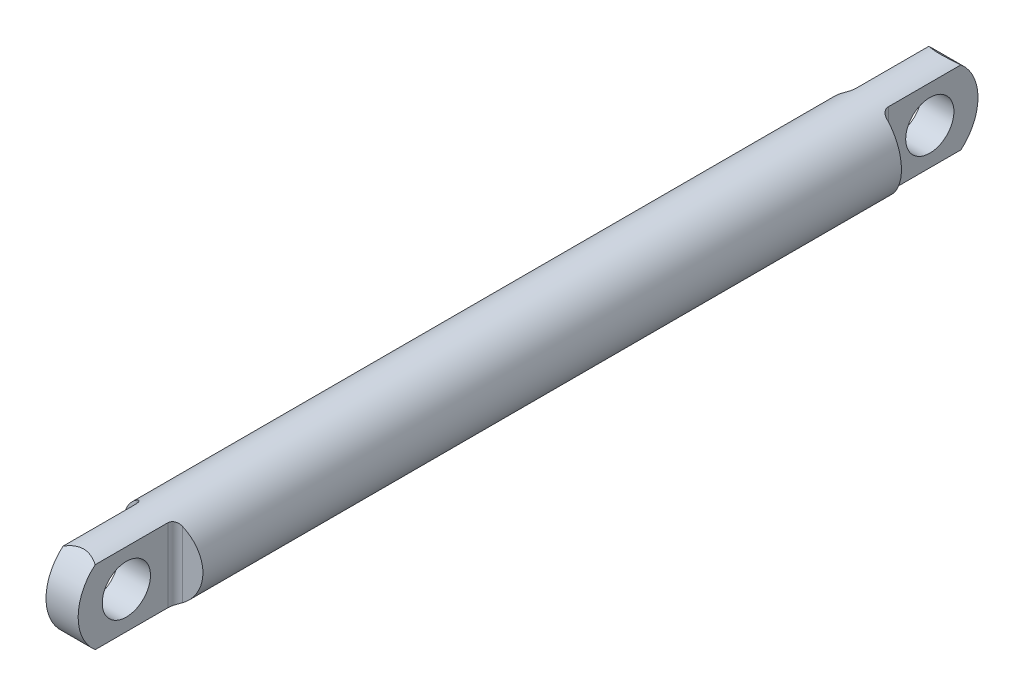
SolidWorks part; units mm, degrees
material "AISI 1045 Steel, cold drawn"
ref_plane "Front Plane" through (0, 0, 0) normal (0, 0, 1) x (1, 0, 0)
ref_plane "Top Plane" through (0, 0, 0) normal (0, 1, 0) x (1, 0, 0)
ref_plane "Right Plane" through (0, 0, 0) normal (1, 0, 0) x (0, 0, -1)
sketch "Sketch1" plane through (0, 0, 0) normal (0, 0, 1) x (1, 0, 0)
  circle A0 centre (0, 0) radius 5
  dimension "D1" = 10
extrude "Boss-Extrude1" add sketch "Sketch1" along normal mid plane 112
sketch "Sketch6" plane through (0, 0, 0) normal (1, 0, 0) x (0, 0, -1)
  line L8 (56, 5) -> (56, -5)
  line L10 (-56, -5) -> (56, -5) construction
  line L12 (56, 5) -> (-56, 5) construction
  line L13 (56, 5) -> (53.3166, 5)
  line L15 (56, -5) -> (53.3166, -5)
  arc A1 (53.3166, -5) -> (53.3166, 5) centre (50, 0) ccw
  dimension "D1" = 6
extrude "Cut-Extrude2" cut sketch "Sketch6" against normal through all and the other way through all
sketch "Sketch7" plane through (0, 0, 0) normal (0, 1, 0) x (1, 0, 0)
  line L0 (-2, 56) -> (-2, 44)
  line L4 (-5, 56) -> (-5, -56) construction
  line L5 (-5, 43.471) -> (-5, 56)
  line L6 (-5, 56) -> (-2, 56)
  line L7 (0, 3.0864) -> (0, -9.0403) construction
  line L8 (5, 56) -> (2, 56)
  line L9 (2, 56) -> (2, 44)
  line L16 (-5, 43.471) -> (-2, 44)
  line L21 (2, 44) -> (5, 43.471)
  line L22 (5, -56) -> (5, 56) construction
  line L23 (5, 43.471) -> (5, 56)
  dimension "D3" = 100
  dimension "D2" = 12
  dimension "D1" = 2
  dimension "D4" = 100
  dimension "D5" = 2
extrude "Cut-Extrude3" cut sketch "Sketch7" against normal through all both and the other way through all
sketch "Sketch8" plane through (-2, 0, 0) normal (1, 0, 0) x (0, 0, -1)
  circle A0 centre (50, 0) radius 3
  arc A7 (53.873, -4.5826) -> (53.873, 4.5826) centre (50, 0) ccw construction
  dimension "D1" = 6
extrude "Cut-Extrude4" cut sketch "Sketch8" against normal through all both and the other way through all contours A0
fillet "Fillet1" radius 1 2 edges at (-2, 0, -44) (2, 0, -44)
mirror "Mirror2" about plane through (0, 0, 0) normal (0, 0, 1) of "Fillet1", "Cut-Extrude3", "Cut-Extrude2", "Cut-Extrude4"
equation "\"D4@Sketch7\"=\"D3@Sketch7\""
equation "\"D5@Sketch7\"=\"D1@Sketch7\""
